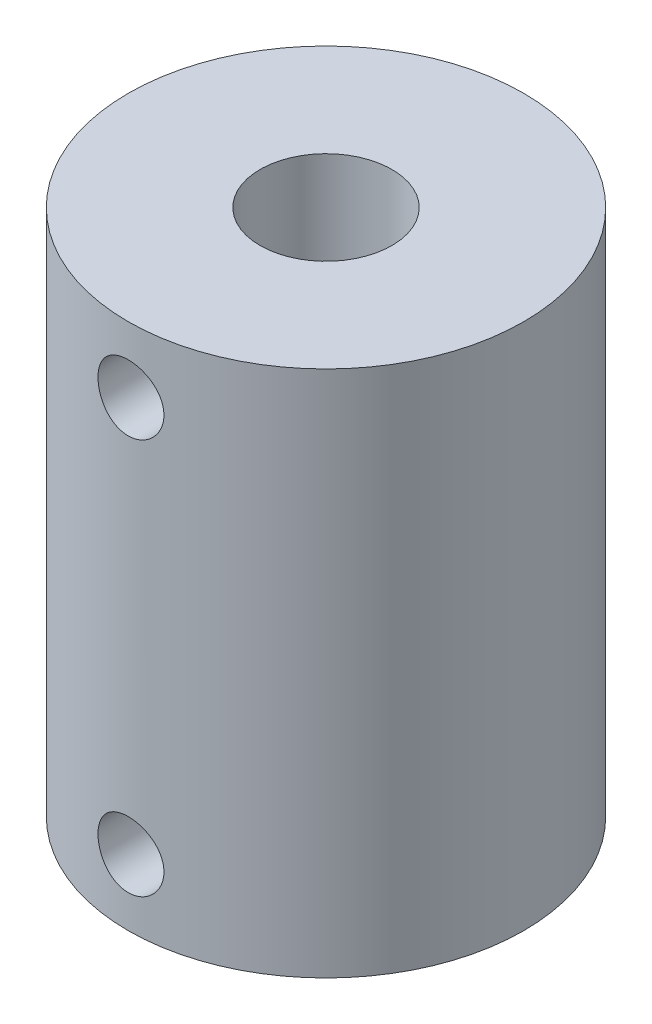
SolidWorks part; units mm, degrees
ref_plane "Front Plane" through (0, 0, 0) normal (0, 0, 1) x (1, 0, 0)
ref_plane "Top Plane" through (0, 0, 0) normal (0, 1, 0) x (1, 0, 0)
ref_plane "Right Plane" through (0, 0, 0) normal (1, 0, 0) x (0, 0, -1)
sketch "Sketch1" plane through (0, 0, 0) normal (0, 1, 0) x (1, 0, 0)
  circle A0 centre (0, 0) radius 9.525
  dimension "D1" = 19.05
extrude "Boss-Extrude1" add sketch "Sketch1" along normal blind 25.4
sketch "Sketch2" plane through (0, 25.4, 0) normal (0, 1, 0) x (1, 0, 0)
  circle A0 centre (0, 0) radius 3.175
  dimension "D1" = 6.35
extrude "Cut-Extrude1" cut sketch "Sketch2" against normal blind 12.7
sketch "Sketch4" plane through (0, 0, 0) normal (0, 0, 1) x (1, 0, 0)
  line L0 (0, 0) -> (0, 25.4) construction
  line L1 (3.175, 25.4) -> (-3.175, 25.4) construction
  line L2 (9.525, 25.4) -> (-9.525, 25.4) construction
  circle A0 centre (0, 22.225) radius 1.5875
  circle A1 centre (0, 3.175) radius 1.5875
  dimension "D1" = 3.175
  dimension "D2" = 19.05
  dimension "D3" = 3.175
extrude "Cut-Extrude2" cut sketch "Sketch4" along normal through all
sketch "Sketch5" plane through (0, 12.7, 0) normal (0, 1, 0) x (1, 0, 0)
  circle A0 centre (0, 0) radius 3.0162
  dimension "D1" = 6.0325
extrude "Cut-Extrude3" cut sketch "Sketch5" against normal through all
